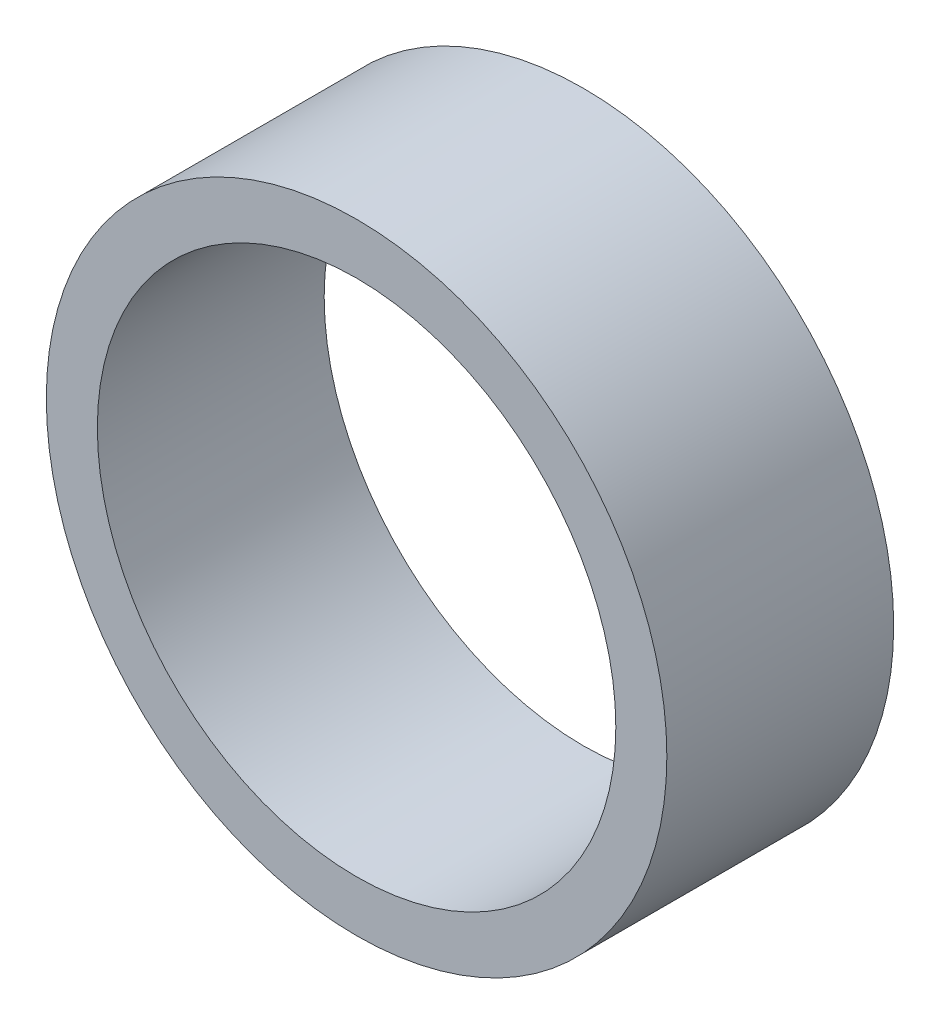
SolidWorks part; units mm, degrees
ref_plane "Front Plane" through (0, 0, 0) normal (0, 0, 1) x (1, 0, 0)
ref_plane "Top Plane" through (0, 0, 0) normal (0, 1, 0) x (1, 0, 0)
ref_plane "Right Plane" through (0, 0, 0) normal (1, 0, 0) x (0, 0, -1)
sketch "Sketch1" plane through (0, 0, 0) normal (0, 0, 1) x (1, 0, 0)
  circle A0 centre (0, 0) radius 20.32
  circle A1 centre (0, 0) radius 24.3205
  dimension "D1" = 40.64
  dimension "D2" = 48.641
extrude "Boss-Extrude1" add sketch "Sketch1" along normal blind 17.78
